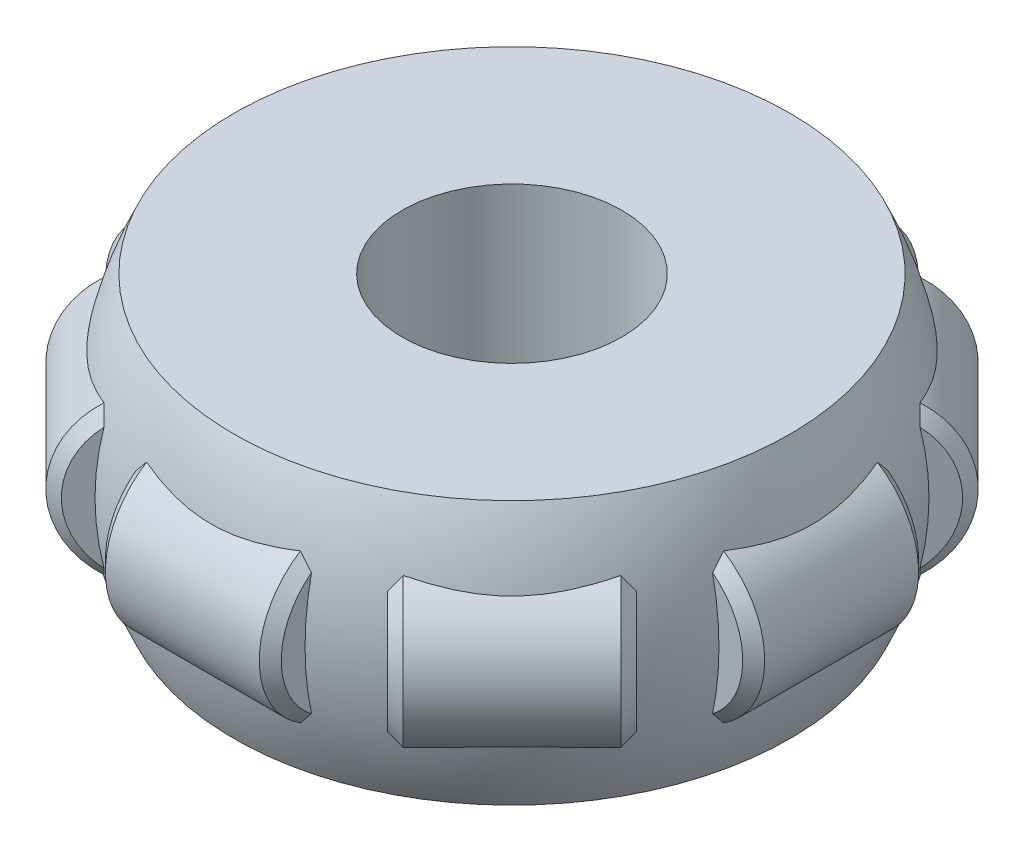
SolidWorks part; units mm, degrees
ref_plane "前视基准面" through (0, 0, 0) normal (0, 0, 1) x (1, 0, 0)
ref_plane "上视基准面" through (0, 0, 0) normal (0, 1, 0) x (1, 0, 0)
ref_plane "右视基准面" through (0, 0, 0) normal (1, 0, 0) x (0, 0, -1)
sketch "草图5" plane through (0, 0, 0) normal (0, 0, 1) x (1, 0, 0)
  line L0 (0, 0) -> (0, 20.7672) construction
  line L1 (0, 0) -> (30.5558, 0) construction
  line L2 (5, 6) -> (5, -6)
  line L3 (5, -6) -> (12.6491, -6)
  line L4 (5, 6) -> (12.6491, 6)
  arc A0 (12.6491, 6) -> (12.6491, -6) centre (0, 0) cw
  dimension "D1" = 5
  dimension "D2" = 14
  dimension "D3" = 12
revolve "旋转1" add sketch "草图5" angle 360 about L0
sketch "草图3" plane through (0, 0, 0) normal (0, 1, 0) x (1, 0, 0)
  line L0 (-4, 11) -> (4, 11)
  line L1 (0, 0) -> (0, 27.0801) construction
  line L2 (4, 11) -> (4, 15)
  line L3 (-4, 15) -> (-4, 11)
  line L4 (-4, 15) -> (4, 15)
  dimension "D1" = 15
  dimension "D2" = 8
  dimension "D3" = 4
revolve "旋转2" add sketch "草图3" angle 360 about L0
chamfer "倒角1" distance 0.5 angle 45 2 edges at (-4, 0, -15) (4, 0, -15)
pattern_circular "阵列(圆周)1" count 8 over 360 about axis through (0, 0, 0) along (0, 1, 0) of "倒角1", "旋转2"
